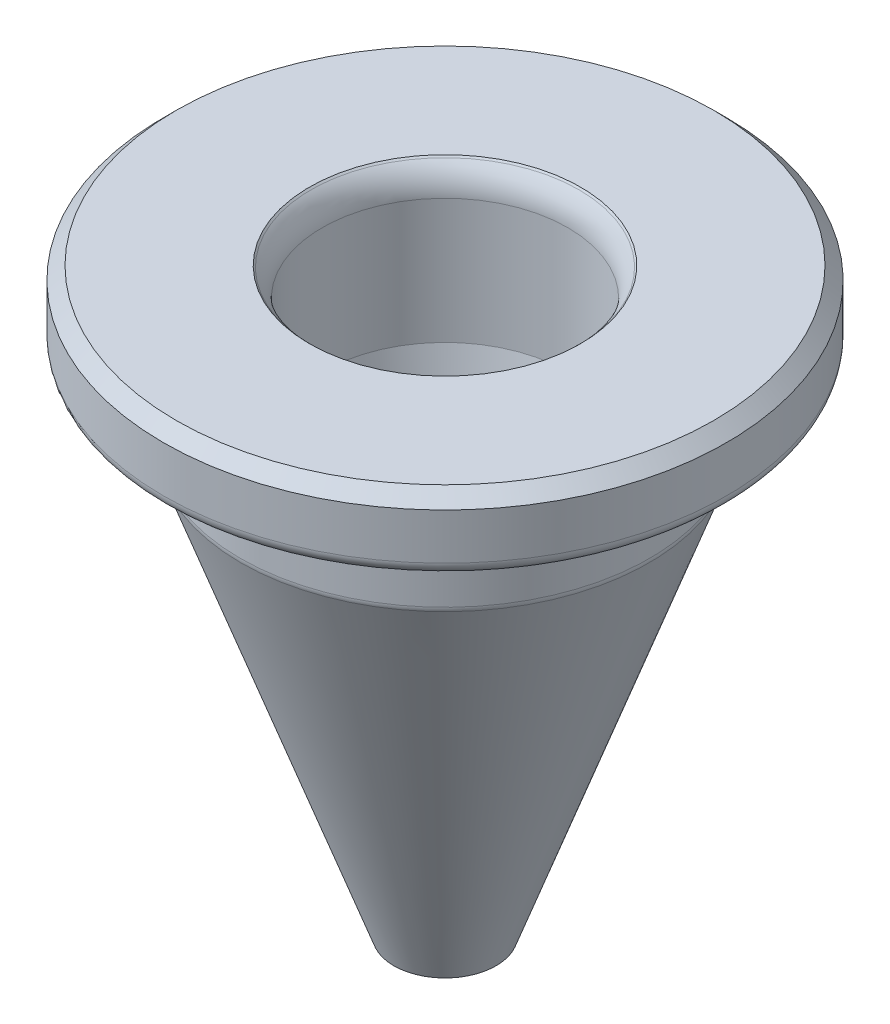
SolidWorks part; units mm, degrees
ref_plane "Ebene vorne" through (0, 0, 0) normal (0, 0, 1) x (1, 0, 0)
ref_plane "Ebene oben" through (0, 0, 0) normal (0, 1, 0) x (1, 0, 0)
ref_plane "Ebene rechts" through (0, 0, 0) normal (1, 0, 0) x (0, 0, -1)
sketch "Skizze1" plane through (0, 0, 0) normal (0, 0, 1) x (1, 0, 0)
  line L0 (0, 0) -> (0, 22) construction
  line L1 (1.5, 0) -> (4.8, 17)
  line L2 (4.8, 17) -> (4.8, 22)
  line L3 (4.8, 22) -> (8, 22)
  line L5 (8, 22) -> (8, 17)
  line L7 (1.5, 0) -> (2, 0.3)
  line L8 (2, 0.3) -> (8, 17)
  dimension "D1" = 9.6
  dimension "D2" = 22
  dimension "D3" = 5
  dimension "D4" = 3
  dimension "D5" = 16
  dimension "D6" = 0.5
  dimension "D7" = 0.3
revolve "Rotation1" add sketch "Skizze1" angle 360 about L0
other "Fläche verschieben1" face at (0, 22, -4.8) parameters "D1"=1
sketch "Skizze2" plane through (0, 23, 0) normal (0, 1, 0) x (1, 0, 0)
  circle A0 centre (0, 0) radius 11
  circle A1 centre (0, 0) radius 4.8
  dimension "D1" = 9.6
  dimension "D2" = 22
extrude "Aufsatz-Linear austragen1" add sketch "Skizze2" against normal blind 2.8
fillet "Verrundung1" radius 0.5 3 edges at (0, 20.2, 11) (0, 20.2, 8) (0, 17, -8)
ref_plane "Ebene1" through (0, 0, 0) normal (0, 0, 1) x (1, 0, 0)
chamfer "Fase1" distance 0.5 angle 45 2 edges at (0, 23, 4.8) (0, 23, 11)
fillet "Verrundung2" radius 1.5 1 edges at (0, 22.5, 4.8)
